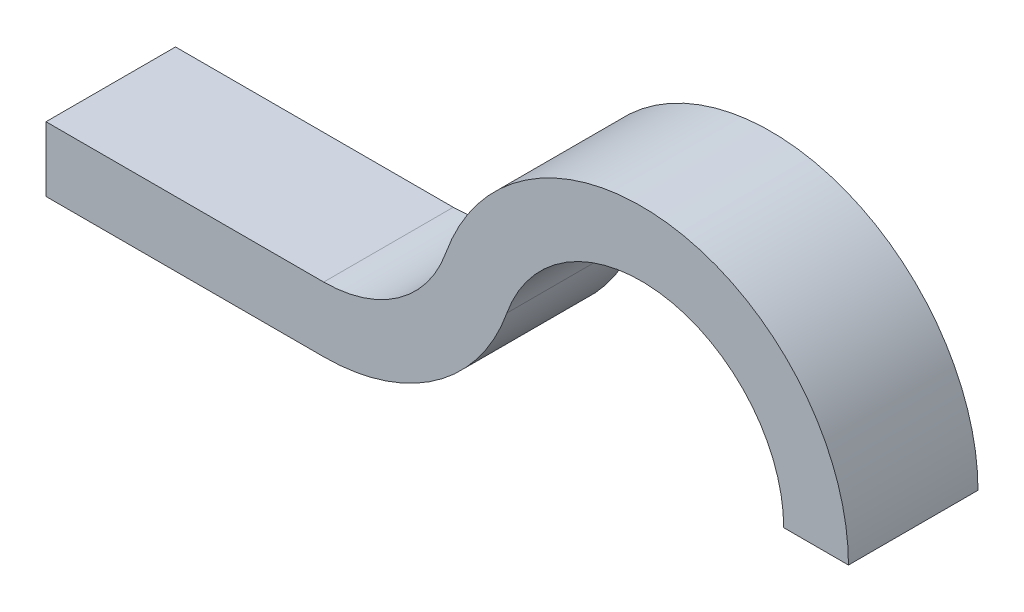
SolidWorks part; units mm, degrees
ref_plane "Plane1" through (0, 0, 0) normal (0, 0, 1) x (1, 0, 0)
ref_plane "Plane2" through (0, 0, 0) normal (0, 1, 0) x (1, 0, 0)
ref_plane "Plane3" through (0, 0, 0) normal (1, 0, 0) x (0, 0, -1)
other "Configuration Table"
sketch "Sketch1" plane through (0, 0, 0) normal (0, 0, 1) x (1, 0, 0)
  line L0 (-24.513, -6.3333) -> (-45.9536, -6.3333)
  line L1 (-45.9536, -1.3333) -> (-45.9536, -6.3333)
  line L2 (16, 0) -> (11, 0)
  line L4 (-24.513, -1.3333) -> (-45.9536, -1.3333)
  arc A0 (-15.0849, 5.3333) -> (16, 0) centre (0, 0) cw
  arc A1 (-15.0849, 5.3333) -> (-24.513, -1.3333) centre (-24.513, 8.6667) cw
  arc A2 (-10.3709, 3.6667) -> (-24.513, -6.3333) centre (-24.513, 8.6667) cw
  arc A3 (-10.3709, 3.6667) -> (11, 0) centre (0, 0) cw
  dimension "D1" = 16
  dimension "D2" = 10
  dimension "D4" = 5
extrude "Base-Extrude" add sketch "Sketch1" along normal blind 10
